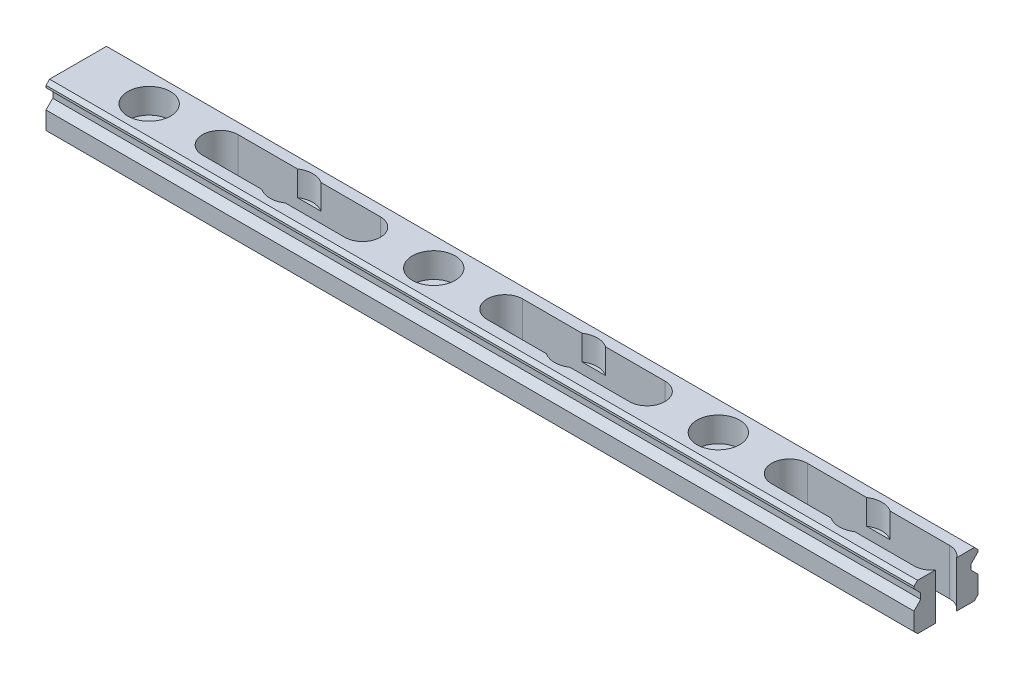
SolidWorks part; units mm, degrees
material "钒"
ref_plane "前视基准面" through (0, 0, 0) normal (0, 0, 1) x (1, 0, 0)
ref_plane "上视基准面" through (0, 0, 0) normal (0, 1, 0) x (1, 0, 0)
ref_plane "右视基准面" through (0, 0, 0) normal (1, 0, 0) x (0, 0, -1)
sketch "草图1" plane through (0, 0, 0) normal (1, 0, 0) x (0, 0, -1)
  line L1 (4.5, -3.25) -> (-4.5, -3.25)
  line L2 (4.5, -3.25) -> (4.5, 3.25)
  line L3 (4.5, 3.25) -> (-4.5, 3.25)
  line L4 (-4.5, -3.25) -> (-4.5, 3.25)
  line L5 (4.5, -3.25) -> (-4.5, 3.25) construction
  line L6 (4.5, 3.25) -> (-4.5, -3.25) construction
  point P0 (0, 0)
  dimension "D1" = 9
  dimension "D2" = 6.5
extrude "拉伸1" add sketch "草图1" along normal blind 122
sketch "草图2" plane through (0, -3.25, 0) normal (0, -1, 0) x (1, 0, 0)
  line L0 (0, 4.5) -> (0, -4.5) construction
  circle A0 centre (10, 0) radius 1.75
  circle A1 centre (30, 0) radius 1.75
  circle A2 centre (50, 0) radius 1.75
  circle A3 centre (70, 0) radius 1.75
  circle A4 centre (90, 0) radius 1.75
  circle A5 centre (110, 0) radius 1.75
  circle A6 centre (130, 0) radius 1.75
  circle A7 centre (150, 0) radius 1.75
  circle A8 centre (170, 0) radius 1.75
  circle A9 centre (190, 0) radius 1.75
  circle A10 centre (210, 0) radius 1.75
  circle A11 centre (230, 0) radius 1.75
  circle A12 centre (250, 0) radius 1.75
  circle A13 centre (270, 0) radius 1.75
  circle A14 centre (290, 0) radius 1.75
  circle A15 centre (310, 0) radius 1.75
  circle A16 centre (330, 0) radius 1.75
  circle A17 centre (350, 0) radius 1.75
  circle A18 centre (370, 0) radius 1.75
  circle A19 centre (390, 0) radius 1.75
  circle A20 centre (410, 0) radius 1.75
  circle A21 centre (430, 0) radius 1.75
  circle A22 centre (450, 0) radius 1.75
  circle A23 centre (470, 0) radius 1.75
  circle A24 centre (490, 0) radius 1.75
  circle A25 centre (510, 0) radius 1.75
  circle A26 centre (530, 0) radius 1.75
  circle A27 centre (550, 0) radius 1.75
  circle A28 centre (570, 0) radius 1.75
  circle A29 centre (590, 0) radius 1.75
  circle A30 centre (610, 0) radius 1.75
  circle A31 centre (630, 0) radius 1.75
  circle A32 centre (650, 0) radius 1.75
  circle A33 centre (670, 0) radius 1.75
  circle A34 centre (690, 0) radius 1.75
  circle A35 centre (710, 0) radius 1.75
  circle A36 centre (730, 0) radius 1.75
  circle A37 centre (750, 0) radius 1.75
  circle A38 centre (770, 0) radius 1.75
  circle A39 centre (790, 0) radius 1.75
  circle A40 centre (810, 0) radius 1.75
  circle A41 centre (830, 0) radius 1.75
  circle A42 centre (850, 0) radius 1.75
  circle A43 centre (870, 0) radius 1.75
  circle A44 centre (890, 0) radius 1.75
  circle A45 centre (910, 0) radius 1.75
  circle A46 centre (930, 0) radius 1.75
  circle A47 centre (950, 0) radius 1.75
  circle A48 centre (970, 0) radius 1.75
  circle A49 centre (990, 0) radius 1.75
  circle A50 centre (1010, 0) radius 1.75
  circle A51 centre (1030, 0) radius 1.75
  circle A52 centre (1050, 0) radius 1.75
  circle A53 centre (1070, 0) radius 1.75
  circle A54 centre (1090, 0) radius 1.75
  circle A55 centre (1110, 0) radius 1.75
  circle A56 centre (1130, 0) radius 1.75
  circle A57 centre (1150, 0) radius 1.75
  circle A58 centre (1170, 0) radius 1.75
  circle A59 centre (1190, 0) radius 1.75
  dimension "D1" = 10
  dimension "D2" = 3.5
  dimension "D3" = 50
  dimension "D4" = 11
extrude "拉伸2" cut sketch "草图2" against normal blind 8
sketch "草图3" plane through (0, 3.25, 0) normal (0, -1, 0) x (1, 0, 0)
  circle A0 centre (10, 0) radius 3
  circle A1 centre (10, 0) radius 1.75 construction
  circle A2 centre (30, 0) radius 3
  circle A3 centre (50, 0) radius 3
  circle A4 centre (70, 0) radius 3
  circle A5 centre (90, 0) radius 3
  circle A6 centre (110, 0) radius 3
  circle A7 centre (130, 0) radius 3
  circle A8 centre (150, 0) radius 3
  circle A9 centre (170, 0) radius 3
  circle A10 centre (190, 0) radius 3
  circle A11 centre (210, 0) radius 3
  circle A12 centre (230, 0) radius 3
  circle A13 centre (250, 0) radius 3
  circle A14 centre (270, 0) radius 3
  circle A15 centre (290, 0) radius 3
  circle A16 centre (310, 0) radius 3
  circle A17 centre (330, 0) radius 3
  circle A18 centre (350, 0) radius 3
  circle A19 centre (370, 0) radius 3
  circle A20 centre (390, 0) radius 3
  circle A21 centre (410, 0) radius 3
  circle A22 centre (430, 0) radius 3
  circle A23 centre (450, 0) radius 3
  circle A24 centre (470, 0) radius 3
  circle A25 centre (490, 0) radius 3
  circle A26 centre (510, 0) radius 3
  circle A27 centre (530, 0) radius 3
  circle A28 centre (550, 0) radius 3
  circle A29 centre (570, 0) radius 3
  circle A30 centre (590, 0) radius 3
  circle A31 centre (610, 0) radius 3
  circle A32 centre (630, 0) radius 3
  circle A33 centre (650, 0) radius 3
  circle A34 centre (670, 0) radius 3
  circle A35 centre (690, 0) radius 3
  circle A36 centre (710, 0) radius 3
  circle A37 centre (730, 0) radius 3
  circle A38 centre (750, 0) radius 3
  circle A39 centre (770, 0) radius 3
  circle A40 centre (790, 0) radius 3
  circle A41 centre (810, 0) radius 3
  circle A42 centre (830, 0) radius 3
  circle A43 centre (850, 0) radius 3
  circle A44 centre (870, 0) radius 3
  circle A45 centre (890, 0) radius 3
  circle A46 centre (910, 0) radius 3
  circle A47 centre (930, 0) radius 3
  circle A48 centre (950, 0) radius 3
  circle A49 centre (970, 0) radius 3
  circle A50 centre (990, 0) radius 3
  circle A51 centre (1010, 0) radius 3
  circle A52 centre (1030, 0) radius 3
  circle A53 centre (1050, 0) radius 3
  circle A54 centre (1070, 0) radius 3
  circle A55 centre (1090, 0) radius 3
  circle A56 centre (1110, 0) radius 3
  circle A57 centre (1130, 0) radius 3
  circle A58 centre (1150, 0) radius 3
  circle A59 centre (1170, 0) radius 3
  circle A60 centre (1190, 0) radius 3
  dimension "D1" = 6
  dimension "D2" = 50
  dimension "D3" = 11
extrude "拉伸3" cut sketch "草图3" along normal blind 3.5
chamfer "倒角1" distance 0.5 angle 45 4 edges at (61, -3.25, 4.5) (61, 3.25, 4.5) (61, 3.25, -4.5) (61, -3.25, -4.5)
sketch "草图4" plane through (0, 0, 0) normal (-1, 0, 0) x (0, 0, 1)
  line L0 (-4.5, 2.45) -> (-4.5, -0.25)
  line L1 (4.5, 2.45) -> (4.5, -0.25)
  line L2 (-4.5, -0.25) -> (-3.55, 0.7)
  line L3 (-3.55, 1.5) -> (-4.5, 2.45)
  line L7 (3.55, 1.5) -> (3.55, 0.7)
  line L8 (3.55, 1.5) -> (4.5, 2.45)
  line L11 (-3.55, 1.5) -> (-3.55, 0.7)
  line L12 (4.5, -0.25) -> (3.55, 0.7)
extrude "切除-拉伸2" cut sketch "草图4" against normal through all
sketch "草图5" plane through (0, 3.25, 0) normal (0, 1, 0) x (1, 0, 0)
  line L0 (60, -2.5) -> (80, -2.5)
  line L1 (20, -2.5) -> (40, -2.5)
  line L2 (20, -2.5) -> (20, 2.5) construction
  line L3 (20, 2.5) -> (40, 2.5)
  line L4 (40, -2.5) -> (40, 2.5) construction
  line L5 (20, -2.5) -> (40, 2.5) construction
  line L6 (20, 2.5) -> (40, -2.5) construction
  line L7 (60, 2.5) -> (80, 2.5)
  line L8 (60, -2.5) -> (60, 2.5) construction
  line L9 (80, -2.5) -> (80, 2.5) construction
  line L10 (60, -2.5) -> (80, 2.5) construction
  line L11 (60, 2.5) -> (80, -2.5) construction
  line L12 (100, -2.5) -> (120, -2.5)
  line L13 (100, 2.5) -> (120, 2.5)
  line L14 (100, -2.5) -> (100, 2.5) construction
  line L15 (120, -2.5) -> (120, 2.5) construction
  line L16 (100, -2.5) -> (120, 2.5) construction
  line L17 (100, 2.5) -> (120, -2.5) construction
  line L18 (140, -2.5) -> (160, -2.5)
  line L19 (140, 2.5) -> (160, 2.5)
  line L20 (140, -2.5) -> (140, 2.5) construction
  line L21 (160, -2.5) -> (160, 2.5) construction
  line L22 (140, -2.5) -> (160, 2.5) construction
  line L23 (140, 2.5) -> (160, -2.5) construction
  line L24 (180, -2.5) -> (200, -2.5)
  line L25 (180, 2.5) -> (200, 2.5)
  line L26 (180, -2.5) -> (180, 2.5) construction
  line L27 (200, -2.5) -> (200, 2.5) construction
  line L28 (180, -2.5) -> (200, 2.5) construction
  line L29 (180, 2.5) -> (200, -2.5) construction
  line L30 (220, -2.5) -> (240, -2.5)
  line L31 (220, 2.5) -> (240, 2.5)
  line L32 (220, -2.5) -> (220, 2.5) construction
  line L33 (240, -2.5) -> (240, 2.5) construction
  line L34 (220, -2.5) -> (240, 2.5) construction
  line L35 (220, 2.5) -> (240, -2.5) construction
  line L36 (260, -2.5) -> (280, -2.5)
  line L37 (260, 2.5) -> (280, 2.5)
  line L38 (260, -2.5) -> (260, 2.5) construction
  line L39 (280, -2.5) -> (280, 2.5) construction
  line L40 (260, -2.5) -> (280, 2.5) construction
  line L41 (260, 2.5) -> (280, -2.5) construction
  line L42 (300, -2.5) -> (320, -2.5)
  line L43 (300, 2.5) -> (320, 2.5)
  line L44 (300, -2.5) -> (300, 2.5) construction
  line L45 (320, -2.5) -> (320, 2.5) construction
  line L46 (300, -2.5) -> (320, 2.5) construction
  line L47 (300, 2.5) -> (320, -2.5) construction
  line L48 (340, -2.5) -> (360, -2.5)
  line L49 (340, 2.5) -> (360, 2.5)
  line L50 (340, -2.5) -> (340, 2.5) construction
  line L51 (360, -2.5) -> (360, 2.5) construction
  line L52 (340, -2.5) -> (360, 2.5) construction
  line L53 (340, 2.5) -> (360, -2.5) construction
  line L54 (380, -2.5) -> (400, -2.5)
  line L55 (380, 2.5) -> (400, 2.5)
  line L56 (380, -2.5) -> (380, 2.5) construction
  line L57 (400, -2.5) -> (400, 2.5) construction
  line L58 (380, -2.5) -> (400, 2.5) construction
  line L59 (380, 2.5) -> (400, -2.5) construction
  line L60 (420, -2.5) -> (440, -2.5)
  line L61 (420, 2.5) -> (440, 2.5)
  line L62 (420, -2.5) -> (420, 2.5) construction
  line L63 (440, -2.5) -> (440, 2.5) construction
  line L64 (420, -2.5) -> (440, 2.5) construction
  line L65 (420, 2.5) -> (440, -2.5) construction
  line L66 (460, -2.5) -> (480, -2.5)
  line L67 (460, 2.5) -> (480, 2.5)
  line L68 (460, -2.5) -> (460, 2.5) construction
  line L69 (480, -2.5) -> (480, 2.5) construction
  line L70 (460, -2.5) -> (480, 2.5) construction
  line L71 (460, 2.5) -> (480, -2.5) construction
  line L72 (500, -2.5) -> (520, -2.5)
  line L73 (500, 2.5) -> (520, 2.5)
  line L74 (500, -2.5) -> (500, 2.5) construction
  line L75 (520, -2.5) -> (520, 2.5) construction
  line L76 (500, -2.5) -> (520, 2.5) construction
  line L77 (500, 2.5) -> (520, -2.5) construction
  line L78 (540, -2.5) -> (560, -2.5)
  line L79 (540, 2.5) -> (560, 2.5)
  line L80 (540, -2.5) -> (540, 2.5) construction
  line L81 (560, -2.5) -> (560, 2.5) construction
  line L82 (540, -2.5) -> (560, 2.5) construction
  line L83 (540, 2.5) -> (560, -2.5) construction
  line L84 (580, -2.5) -> (600, -2.5)
  line L85 (580, 2.5) -> (600, 2.5)
  line L86 (580, -2.5) -> (580, 2.5) construction
  line L87 (600, -2.5) -> (600, 2.5) construction
  line L88 (580, -2.5) -> (600, 2.5) construction
  line L89 (580, 2.5) -> (600, -2.5) construction
  line L90 (620, -2.5) -> (640, -2.5)
  line L91 (620, 2.5) -> (640, 2.5)
  line L92 (620, -2.5) -> (620, 2.5) construction
  line L93 (640, -2.5) -> (640, 2.5) construction
  line L94 (620, -2.5) -> (640, 2.5) construction
  line L95 (620, 2.5) -> (640, -2.5) construction
  line L96 (660, -2.5) -> (680, -2.5)
  line L97 (660, 2.5) -> (680, 2.5)
  line L98 (660, -2.5) -> (660, 2.5) construction
  line L99 (680, -2.5) -> (680, 2.5) construction
  line L100 (660, -2.5) -> (680, 2.5) construction
  line L101 (660, 2.5) -> (680, -2.5) construction
  line L102 (700, -2.5) -> (720, -2.5)
  line L103 (700, 2.5) -> (720, 2.5)
  line L104 (700, -2.5) -> (700, 2.5) construction
  line L105 (720, -2.5) -> (720, 2.5) construction
  line L106 (700, -2.5) -> (720, 2.5) construction
  line L107 (700, 2.5) -> (720, -2.5) construction
  line L108 (740, -2.5) -> (760, -2.5)
  line L109 (740, 2.5) -> (760, 2.5)
  line L110 (740, -2.5) -> (740, 2.5) construction
  line L111 (760, -2.5) -> (760, 2.5) construction
  line L112 (740, -2.5) -> (760, 2.5) construction
  line L113 (740, 2.5) -> (760, -2.5) construction
  line L114 (780, -2.5) -> (800, -2.5)
  line L115 (780, 2.5) -> (800, 2.5)
  line L116 (780, -2.5) -> (780, 2.5) construction
  line L117 (800, -2.5) -> (800, 2.5) construction
  line L118 (780, -2.5) -> (800, 2.5) construction
  line L119 (780, 2.5) -> (800, -2.5) construction
  line L120 (820, -2.5) -> (840, -2.5)
  line L121 (820, 2.5) -> (840, 2.5)
  line L122 (820, -2.5) -> (820, 2.5) construction
  line L123 (840, -2.5) -> (840, 2.5) construction
  line L124 (820, -2.5) -> (840, 2.5) construction
  line L125 (820, 2.5) -> (840, -2.5) construction
  line L126 (860, -2.5) -> (880, -2.5)
  line L127 (860, 2.5) -> (880, 2.5)
  line L128 (860, -2.5) -> (860, 2.5) construction
  line L129 (880, -2.5) -> (880, 2.5) construction
  line L130 (860, -2.5) -> (880, 2.5) construction
  line L131 (860, 2.5) -> (880, -2.5) construction
  line L132 (900, -2.5) -> (920, -2.5)
  line L133 (900, 2.5) -> (920, 2.5)
  line L134 (900, -2.5) -> (900, 2.5) construction
  line L135 (920, -2.5) -> (920, 2.5) construction
  line L136 (900, -2.5) -> (920, 2.5) construction
  line L137 (900, 2.5) -> (920, -2.5) construction
  line L138 (940, -2.5) -> (960, -2.5)
  line L139 (940, 2.5) -> (960, 2.5)
  line L140 (940, -2.5) -> (940, 2.5) construction
  line L141 (960, -2.5) -> (960, 2.5) construction
  line L142 (940, -2.5) -> (960, 2.5) construction
  line L143 (940, 2.5) -> (960, -2.5) construction
  line L144 (980, -2.5) -> (1000, -2.5)
  line L145 (980, 2.5) -> (1000, 2.5)
  line L146 (980, -2.5) -> (980, 2.5) construction
  line L147 (1000, -2.5) -> (1000, 2.5) construction
  line L148 (980, -2.5) -> (1000, 2.5) construction
  line L149 (980, 2.5) -> (1000, -2.5) construction
  line L150 (1020, -2.5) -> (1040, -2.5)
  line L151 (1020, 2.5) -> (1040, 2.5)
  line L152 (1020, -2.5) -> (1020, 2.5) construction
  line L153 (1040, -2.5) -> (1040, 2.5) construction
  line L154 (1020, -2.5) -> (1040, 2.5) construction
  line L155 (1020, 2.5) -> (1040, -2.5) construction
  line L156 (1060, -2.5) -> (1080, -2.5)
  line L157 (1060, 2.5) -> (1080, 2.5)
  line L158 (1060, -2.5) -> (1060, 2.5) construction
  line L159 (1080, -2.5) -> (1080, 2.5) construction
  line L160 (1060, -2.5) -> (1080, 2.5) construction
  line L161 (1060, 2.5) -> (1080, -2.5) construction
  line L162 (1100, -2.5) -> (1120, -2.5)
  line L163 (1100, 2.5) -> (1120, 2.5)
  line L164 (1100, -2.5) -> (1100, 2.5) construction
  line L165 (1120, -2.5) -> (1120, 2.5) construction
  line L166 (1100, -2.5) -> (1120, 2.5) construction
  line L167 (1100, 2.5) -> (1120, -2.5) construction
  line L168 (1140, -2.5) -> (1160, -2.5)
  line L169 (1140, 2.5) -> (1160, 2.5)
  line L170 (1140, -2.5) -> (1140, 2.5) construction
  line L171 (1160, -2.5) -> (1160, 2.5) construction
  line L172 (1140, -2.5) -> (1160, 2.5) construction
  line L173 (1140, 2.5) -> (1160, -2.5) construction
  arc A0 (20, 2.5) -> (20, -2.5) centre (20, 0) ccw
  arc A1 (40, -2.5) -> (40, 2.5) centre (40, 0) ccw
  arc A2 (60, 2.5) -> (60, -2.5) centre (60, 0) ccw
  arc A3 (80, -2.5) -> (80, 2.5) centre (80, 0) ccw
  arc A4 (100, 2.5) -> (100, -2.5) centre (100, 0) ccw
  arc A5 (120, -2.5) -> (120, 2.5) centre (120, 0) ccw
  arc A6 (140, 2.5) -> (140, -2.5) centre (140, 0) ccw
  arc A7 (160, -2.5) -> (160, 2.5) centre (160, 0) ccw
  arc A8 (180, 2.5) -> (180, -2.5) centre (180, 0) ccw
  arc A9 (200, -2.5) -> (200, 2.5) centre (200, 0) ccw
  arc A10 (220, 2.5) -> (220, -2.5) centre (220, 0) ccw
  arc A11 (240, -2.5) -> (240, 2.5) centre (240, 0) ccw
  arc A12 (260, 2.5) -> (260, -2.5) centre (260, 0) ccw
  arc A13 (280, -2.5) -> (280, 2.5) centre (280, 0) ccw
  arc A14 (300, 2.5) -> (300, -2.5) centre (300, 0) ccw
  arc A15 (320, -2.5) -> (320, 2.5) centre (320, 0) ccw
  arc A16 (340, 2.5) -> (340, -2.5) centre (340, 0) ccw
  arc A17 (360, -2.5) -> (360, 2.5) centre (360, 0) ccw
  arc A18 (380, 2.5) -> (380, -2.5) centre (380, 0) ccw
  arc A19 (400, -2.5) -> (400, 2.5) centre (400, 0) ccw
  arc A20 (420, 2.5) -> (420, -2.5) centre (420, 0) ccw
  arc A21 (440, -2.5) -> (440, 2.5) centre (440, 0) ccw
  arc A22 (460, 2.5) -> (460, -2.5) centre (460, 0) ccw
  arc A23 (480, -2.5) -> (480, 2.5) centre (480, 0) ccw
  arc A24 (500, 2.5) -> (500, -2.5) centre (500, 0) ccw
  arc A25 (520, -2.5) -> (520, 2.5) centre (520, 0) ccw
  arc A26 (540, 2.5) -> (540, -2.5) centre (540, 0) ccw
  arc A27 (560, -2.5) -> (560, 2.5) centre (560, 0) ccw
  arc A28 (580, 2.5) -> (580, -2.5) centre (580, 0) ccw
  arc A29 (600, -2.5) -> (600, 2.5) centre (600, 0) ccw
  arc A30 (620, 2.5) -> (620, -2.5) centre (620, 0) ccw
  arc A31 (640, -2.5) -> (640, 2.5) centre (640, 0) ccw
  arc A32 (660, 2.5) -> (660, -2.5) centre (660, 0) ccw
  arc A33 (680, -2.5) -> (680, 2.5) centre (680, 0) ccw
  arc A34 (700, 2.5) -> (700, -2.5) centre (700, 0) ccw
  arc A35 (720, -2.5) -> (720, 2.5) centre (720, 0) ccw
  arc A36 (740, 2.5) -> (740, -2.5) centre (740, 0) ccw
  arc A37 (760, -2.5) -> (760, 2.5) centre (760, 0) ccw
  arc A38 (780, 2.5) -> (780, -2.5) centre (780, 0) ccw
  arc A39 (800, -2.5) -> (800, 2.5) centre (800, 0) ccw
  arc A40 (820, 2.5) -> (820, -2.5) centre (820, 0) ccw
  arc A41 (840, -2.5) -> (840, 2.5) centre (840, 0) ccw
  arc A42 (860, 2.5) -> (860, -2.5) centre (860, 0) ccw
  arc A43 (880, -2.5) -> (880, 2.5) centre (880, 0) ccw
  arc A44 (900, 2.5) -> (900, -2.5) centre (900, 0) ccw
  arc A45 (920, -2.5) -> (920, 2.5) centre (920, 0) ccw
  arc A46 (940, 2.5) -> (940, -2.5) centre (940, 0) ccw
  arc A47 (960, -2.5) -> (960, 2.5) centre (960, 0) ccw
  arc A48 (980, 2.5) -> (980, -2.5) centre (980, 0) ccw
  arc A49 (1000, -2.5) -> (1000, 2.5) centre (1000, 0) ccw
  arc A50 (1020, 2.5) -> (1020, -2.5) centre (1020, 0) ccw
  arc A51 (1040, -2.5) -> (1040, 2.5) centre (1040, 0) ccw
  arc A52 (1060, 2.5) -> (1060, -2.5) centre (1060, 0) ccw
  arc A53 (1080, -2.5) -> (1080, 2.5) centre (1080, 0) ccw
  arc A54 (1100, 2.5) -> (1100, -2.5) centre (1100, 0) ccw
  arc A55 (1120, -2.5) -> (1120, 2.5) centre (1120, 0) ccw
  arc A56 (1140, 2.5) -> (1140, -2.5) centre (1140, 0) ccw
  arc A57 (1160, -2.5) -> (1160, 2.5) centre (1160, 0) ccw
  point P0 (30, 0)
  point P10 (70, 0)
  point P17 (110, 0)
  point P24 (150, 0)
  point P31 (190, 0)
  point P38 (230, 0)
  point P45 (270, 0)
  point P52 (310, 0)
  point P59 (350, 0)
  point P66 (390, 0)
  point P73 (430, 0)
  point P80 (470, 0)
  point P87 (510, 0)
  point P94 (550, 0)
  point P101 (590, 0)
  point P108 (630, 0)
  point P115 (670, 0)
  point P122 (710, 0)
  point P129 (750, 0)
  point P136 (790, 0)
  point P143 (830, 0)
  point P150 (870, 0)
  point P157 (910, 0)
  point P164 (950, 0)
  point P171 (990, 0)
  point P178 (1030, 0)
  point P185 (1070, 0)
  point P192 (1110, 0)
  point P199 (1150, 0)
  dimension "D1" = 20
  dimension "D2" = 5
  dimension "D3" = 25
  dimension "D4" = 5
extrude "切除-拉伸3" cut sketch "草图5" against normal blind 10
